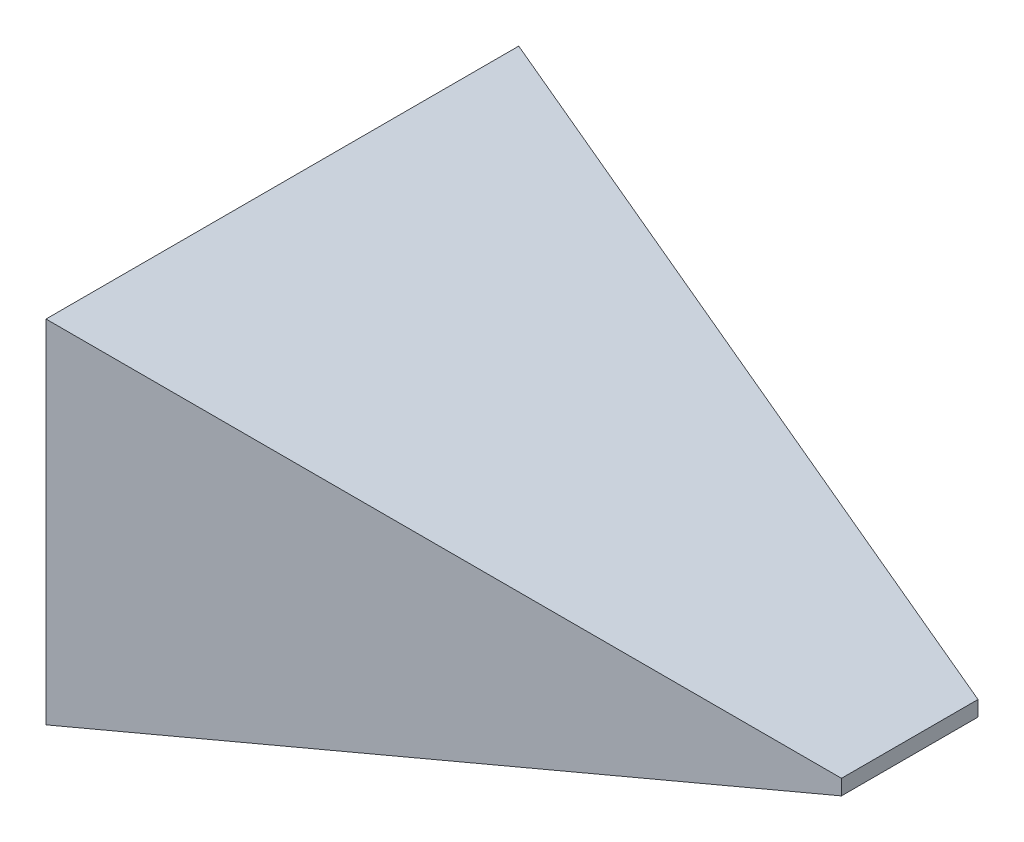
SolidWorks part; units mm, degrees
ref_plane "Front Plane" through (0, 0, 0) normal (0, 0, 1) x (1, 0, 0)
ref_plane "Top Plane" through (0, 0, 0) normal (0, 1, 0) x (1, 0, 0)
ref_plane "Right Plane" through (0, 0, 0) normal (1, 0, 0) x (0, 0, -1)
sketch "Sketch1" plane through (0, 0, 0) normal (1, 0, 0) x (0, 0, -1)
  line L1 (-34.163, -25.4) -> (34.163, -25.4)
  line L2 (-34.163, -25.4) -> (-34.163, 25.4)
  line L3 (-34.163, 25.4) -> (34.163, 25.4)
  line L4 (34.163, -25.4) -> (34.163, 25.4)
  line L5 (-34.163, -25.4) -> (34.163, 25.4) construction
  line L6 (-34.163, 25.4) -> (34.163, -25.4) construction
  point P0 (0, 0)
  dimension "D1" = 50.8
  dimension "D2" = 68.326
extrude "Boss-Extrude1" add sketch "Sketch1" along normal blind 90.678 draft 15
